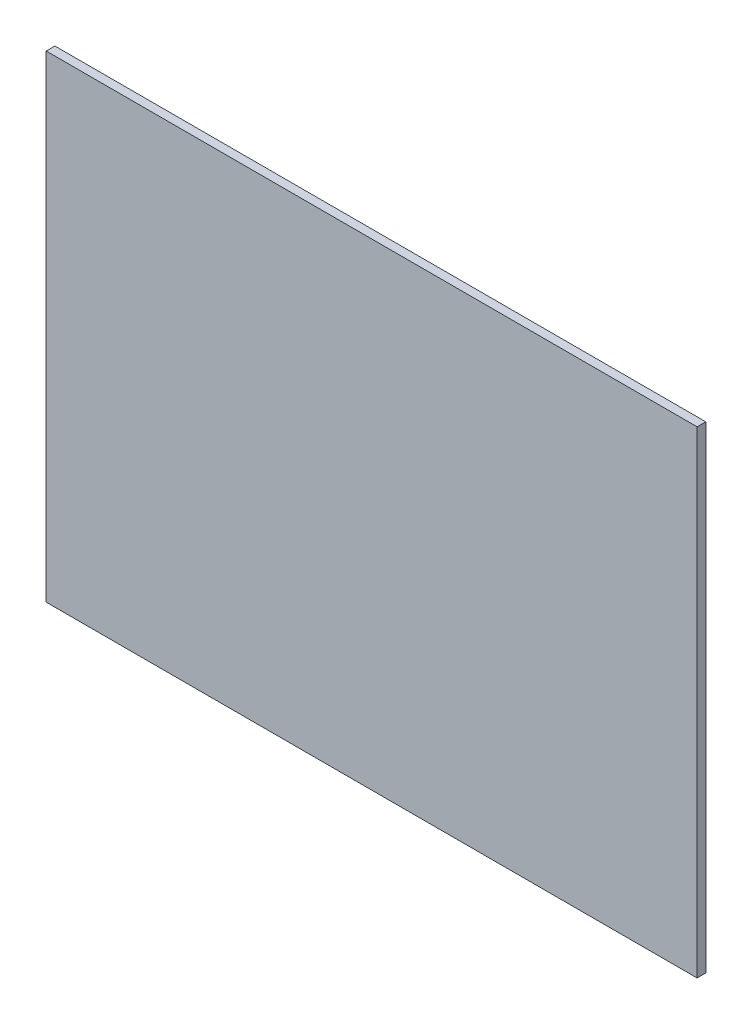
SolidWorks part; units mm, degrees
material "PC High Viscosity"
ref_plane "Front Plane" through (0, 0, 0) normal (0, 0, 1) x (1, 0, 0)
ref_plane "Top Plane" through (0, 0, 0) normal (0, 1, 0) x (1, 0, 0)
ref_plane "Right Plane" through (0, 0, 0) normal (1, 0, 0) x (0, 0, -1)
sketch "Sketch1" plane through (0, 0, 0) normal (0, 0, 1) x (1, 0, 0)
  line L1 (0, 0) -> (381, 0)
  line L2 (0, 0) -> (0, 279.4)
  line L3 (0, 279.4) -> (381, 279.4)
  line L4 (381, 0) -> (381, 279.4)
  dimension "D1" = 381
  dimension "D2" = 279.4
extrude "Boss-Extrude1" add sketch "Sketch1" along normal blind 5.08
sketch "Sketch2" plane through (0, 0, 0) normal (0, 0, -1) x (-1, 0, 0)
  line L0 (0, 279.4) -> (0, 0) construction
  line L1 (-381, 279.4) -> (0, 279.4) construction
  line L2 (-523.4473, 139.7) -> (65.789, 139.7) construction
  circle A0 centre (-12.7, 266.7) radius 2.032
  dimension "D3" = 4.064
  dimension "D1" = 12.7
  dimension "D2" = 12.7
  dimension "D4" = 139.7
